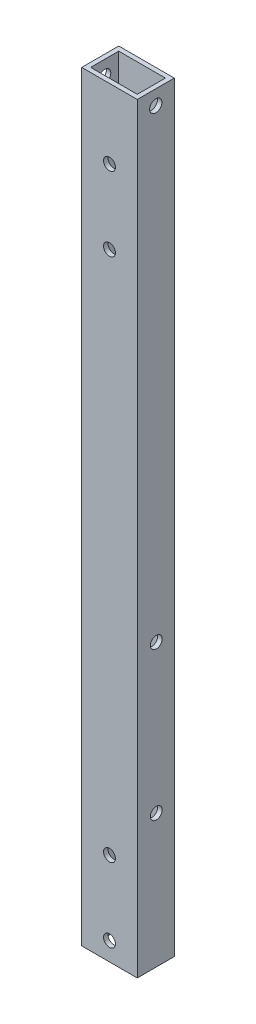
SolidWorks part; units mm, degrees
ref_plane "正面" through (0, 0, 0) normal (0, 0, 1) x (1, 0, 0)
ref_plane "平面" through (0, 0, 0) normal (0, 1, 0) x (1, 0, 0)
ref_plane "右側面" through (0, 0, 0) normal (1, 0, 0) x (0, 0, -1)
sketch "ｽｹｯﾁ1" plane through (0, 0, 0) normal (0, 1, 0) x (1, 0, 0)
  line L0 (-6.3, 3.8) -> (6.3, 3.8)
  line L1 (-7.5, 5) -> (7.5, 5)
  line L2 (-7.5, 5) -> (-7.5, -5)
  line L3 (-7.5, -5) -> (7.5, -5)
  line L4 (7.5, 5) -> (7.5, -5)
  line L5 (-7.5, 5) -> (7.5, -5) construction
  line L6 (-7.5, -5) -> (7.5, 5) construction
  line L7 (6.3, 3.8) -> (6.3, -3.8)
  line L8 (-6.3, -3.8) -> (6.3, -3.8)
  line L9 (-6.3, 3.8) -> (-6.3, -3.8)
  point P0 (0, 0)
  dimension "D1" = 15
  dimension "D2" = 10
  dimension "D3" = 1.2
extrude "ﾎﾞｽ - 押し出し1" add sketch "ｽｹｯﾁ1" along normal mid plane 220
sketch "ｽｹｯﾁ2" plane through (0, 0, -5) normal (0, 0, -1) x (-1, 0, 0)
  line L0 (0, -110) -> (0, -85) construction
  line L1 (-7.5, -110) -> (7.5, -110) construction
  circle A0 centre (0, -85) radius 1.6
  circle A1 centre (0, -105) radius 1.6
  dimension "D2" = 3.2
  dimension "D3" = 3.2
  dimension "D1" = 25
  dimension "D4" = 20
extrude "ｶｯﾄ - 押し出し1" cut sketch "ｽｹｯﾁ2" against normal blind 100
sketch "ｽｹｯﾁ3" plane through (-7.5, 0, 0) normal (-1, 0, 0) x (0, 0, 1)
  line L0 (0, -110) -> (0, 0) construction
  line L1 (-5, -110) -> (5, -110) construction
  circle A0 centre (-0.125, -74) radius 1.6
  circle A1 centre (-0.125, -34) radius 1.6
  dimension "D1" = 3.2
  dimension "D2" = 3.2
extrude "ｶｯﾄ - 押し出し2" cut sketch "ｽｹｯﾁ3" against normal blind 15
sketch "ｽｹｯﾁ5" plane through (0, 110, 0) normal (0, 1, 0) x (1, 0, 0)
  line L4 (7.5, -5) -> (7.5, 5)
  line L5 (7.5, 5) -> (-7.5, 5)
  line L6 (-7.5, 5) -> (-7.5, -5)
  line L7 (-7.5, -5) -> (7.5, -5)
  line L8 (7.5, -5) -> (7.5, 5)
  line L9 (7.5, 5) -> (-7.5, 5)
  line L10 (-7.5, 5) -> (-7.5, -5)
  line L11 (-7.5, -5) -> (7.5, -5)
  dimension "D1" = 0
extrude "ｶｯﾄ - 押し出し4" cut sketch "ｽｹｯﾁ5" against normal blind 14.5
sketch "ｽｹｯﾁ6" plane through (0, 0, -5) normal (0, 0, -1) x (-1, 0, 0)
  line L0 (0, 95.5) -> (0, 90.5) construction
  line L1 (-7.5, 95.5) -> (7.5, 95.5) construction
  line L2 (0, 90.5) -> (0, 76.66) construction
  line L3 (0, 76.66) -> (0, 56.66) construction
  circle A0 centre (0, 90.5) radius 1.6
  circle A1 centre (0, 76.66) radius 1.6
  circle A2 centre (0, 56.66) radius 1.6
  dimension "D2" = 3.2
  dimension "D4" = 3.2
  dimension "D6" = 3.2
  dimension "D1" = 5
  dimension "D3" = 13.84
  dimension "D5" = 20
extrude "ｶｯﾄ - 押し出し5" cut sketch "ｽｹｯﾁ6" against normal blind 15 contours A2 | A1
sketch "ｽｹｯﾁ7" plane through (-7.5, 0, 0) normal (-1, 0, 0) x (0, 0, 1)
  arc A0 (0, 93.15) -> (0, 89.85) centre (0, 91.5) ccw construction
  arc A1 (0, 89.85) -> (0, 93.15) centre (0, 91.5) ccw construction
  arc A2 (0, 93.15) -> (0, 89.85) centre (0, 91.5) ccw
  arc A3 (0, 89.85) -> (0, 93.15) centre (0, 91.5) ccw
extrude "ｶｯﾄ - 押し出し6" cut sketch "ｽｹｯﾁ7" against normal blind 15
